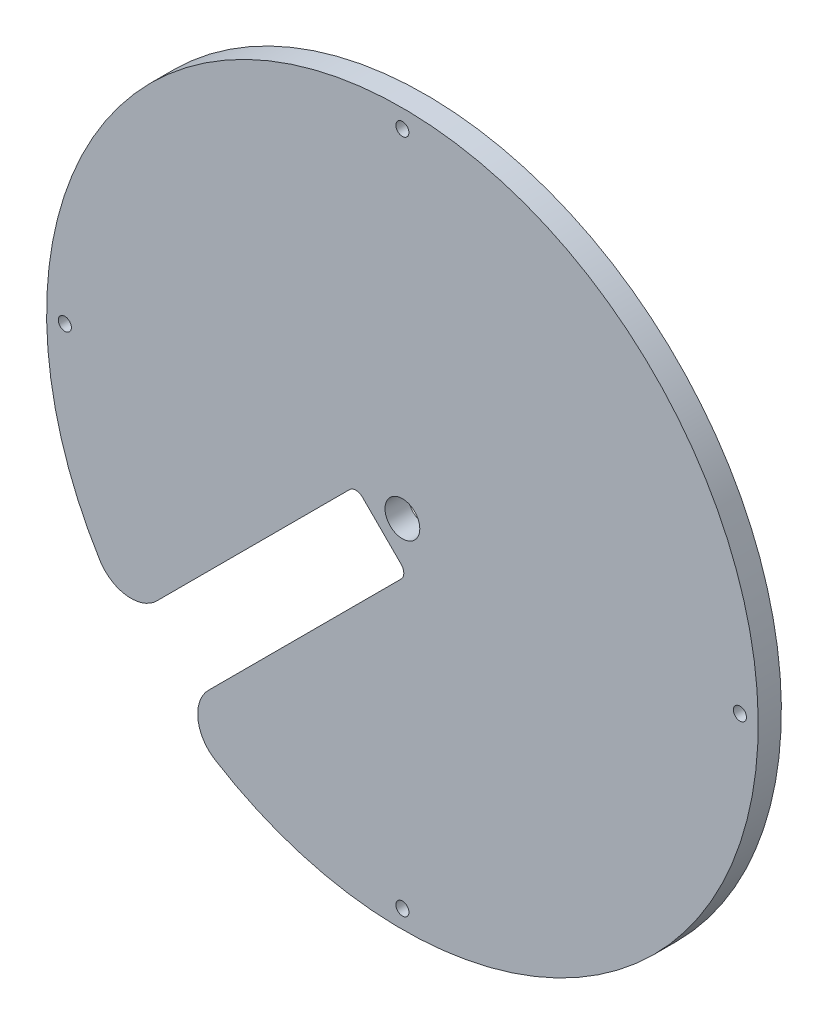
SolidWorks part; units mm, degrees
ref_plane "Front Plane" through (0, 0, 0) normal (0, 0, 1) x (1, 0, 0)
ref_plane "Top Plane" through (0, 0, 0) normal (0, 1, 0) x (1, 0, 0)
ref_plane "Right Plane" through (0, 0, 0) normal (1, 0, 0) x (0, 0, -1)
sketch "Sketch1" plane through (0, 0, 0) normal (0, 0, 1) x (1, 0, 0)
  line L0 (0, 92.5) -> (0, 0) construction
  line L1 (-92.5, 0) -> (0, 0) construction
  circle A0 centre (0, 0) radius 97.5
  circle A5 centre (0, 0) radius 4.7625
  circle A6 centre (0, 92.5) radius 1.7859
  circle A7 centre (92.5, 0) radius 1.7859
  circle A8 centre (0, -92.5) radius 1.7859
  circle A9 centre (-92.5, 0) radius 1.7859
  point P14 (0, 0)
  point P16 (0, 0)
  dimension "D1" = 195
  dimension "D2" = 9.525
  dimension "D3" = 3.5719
  dimension "D5" = 4
  dimension "D4" = 92.5
extrude "Boss-Extrude1" add sketch "Sketch1" along normal blind 6.35
sketch "Sketch2" plane through (0, 0, 6.35) normal (0, 0, 1) x (1, 0, 0)
  circle A0 centre (0, 9.525) radius 1.75
  dimension "D2" = 3.5
  dimension "D1" = 9.525
extrude "Cut-Extrude1" [suppressed] cut sketch "Sketch2" against normal up to next
pattern_circular "CirPattern1" [suppressed] count 6 over 360
sketch "Sketch5" plane through (0, 0, 6.35) normal (0, 0, 1) x (1, 0, 0)
  line L0 (0, 0) -> (-68.9429, -68.9429) construction
  line L1 (1.4142, -12.7279) -> (-64.3467, -78.4889)
  line L2 (-12.7279, 1.4142) -> (-78.4889, -64.3467)
  line L3 (3.4925, 0) -> (-3.4925, 0) construction
  line L4 (0, 0) -> (-5.6569, -5.6569)
  line L5 (-12.7279, 1.4142) -> (1.4142, -12.7279)
  circle A0 centre (0, 0) radius 97.5 construction
  arc A2 (-78.4889, -64.3467) -> (-64.3467, -78.4889) centre (-68.9429, -68.9429) ccw
  point P5 (-35.7089, -35.7089)
  point P18 (-5.6569, -5.6569)
  dimension "D1" = 45
  dimension "D2" = 20
  dimension "D3" = 8
extrude "Cut-Extrude3" cut sketch "Sketch5" against normal up to next
sketch "Sketch7" [suppressed] plane through (0, 0, 6.35) normal (0, 0, 1) x (1, 0, 0)
  line L0 (-0.6031, -7.8822) -> (0.7071, -9.1924)
  line L1 (0.7071, -9.1924) -> (-1.0359, -10.9354)
  arc A0 (-0.6031, -7.8822) -> (-1.0359, -10.9354) centre (0, -9.525) cw
extrude "Boss-Extrude2" [suppressed] add sketch "Sketch7" against normal blind 6.35
fillet "Fillet2" radius 10 2 edges at (-61.5083, -75.6504, 3.175) (-75.6504, -61.5083, 3.175)
fillet "Fillet3" radius 2.5 2 edges at (1.4142, -12.7279, 3.175) (-12.7279, 1.4142, 3.175)
